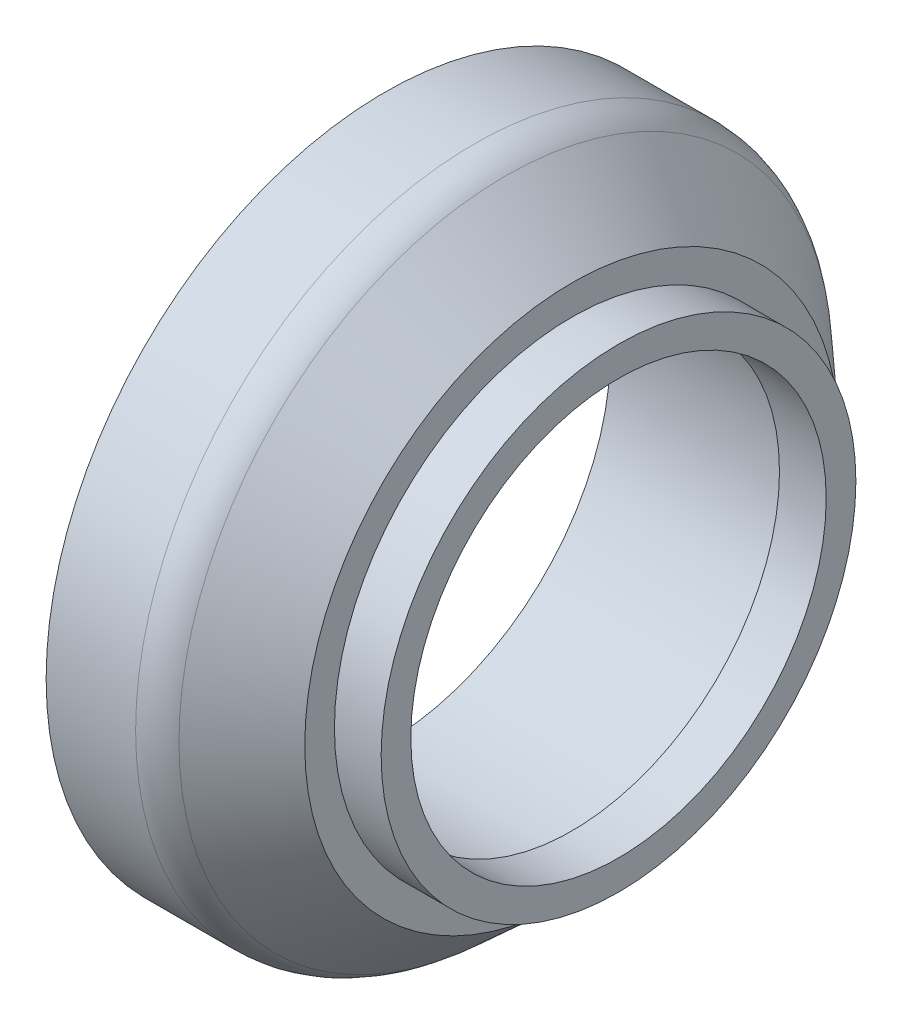
SolidWorks part; units mm, degrees
ref_plane "Front Plane" through (0, 0, 0) normal (0, 0, 1) x (1, 0, 0)
ref_plane "Top Plane" through (0, 0, 0) normal (0, 1, 0) x (1, 0, 0)
ref_plane "Right Plane" through (0, 0, 0) normal (1, 0, 0) x (0, 0, -1)
sketch "Sketch1" plane through (0, 0, 0) normal (0, 0, 1) x (1, 0, 0)
  line L0 (0, 0) -> (44.585, 0) construction
  line L1 (0, 0) -> (0, 48.25) construction
  line L2 (0, 48.25) -> (40, 48.25)
  line L3 (40, 48.25) -> (40, 57.15)
  line L4 (40, 57.15) -> (23, 72.5)
  line L5 (23, 72.5) -> (0, 72.5)
  line L6 (0, 72.5) -> (0, 48.25)
  dimension "D1" = 48.25
  dimension "D2" = 40
  dimension "D3" = 57.15
  dimension "D4" = 72.5
  dimension "D5" = 23
revolve "Revolve1" add sketch "Sketch1" angle 360 about L0
fillet "Fillet1" radius 10 1 edges at (23, 0, 72.5)
sketch "Sketch2" plane through (40, 0, 0) normal (1, 0, 0) x (0, 0, -1)
  circle A0 centre (0, 0) radius 44.45
  circle A1 centre (0, 0) radius 50.8
  dimension "D1" = 101.6
  dimension "D2" = 88.9
extrude "Boss-Extrude1" add sketch "Sketch2" along normal blind 10
sketch "Sketch3" plane through (0, 0, 0) normal (-1, 0, 0) x (0, 0, 1)
  circle A0 centre (0, 1.3171) radius 62.5 construction
  circle A1 centre (0, 63.8171) radius 5.35
  dimension "D1" = 125
  dimension "D2" = 10.7
extrude "Cut-Extrude1" cut sketch "Sketch3" against normal blind 19.4
chamfer "Chamfer1" distance 1 angle 45 1 edges at (0, 63.8171, 5.35)
pattern_circular "CirPattern1" count 12 over 360 about axis through (0, 0, 0) along (1, 0, 0) of "Cut-Extrude1", "Chamfer1"
